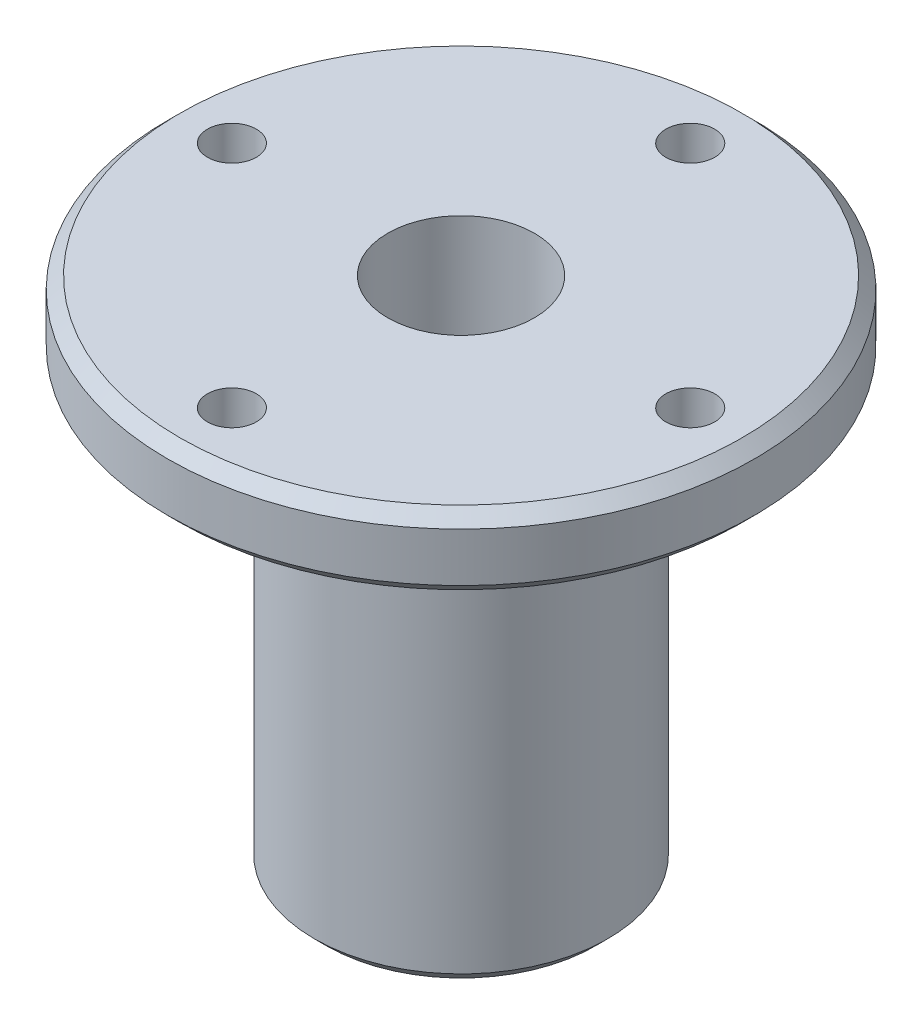
SolidWorks part; units mm, degrees
ref_plane "Front Plane" through (0, 0, 0) normal (0, 0, 1) x (1, 0, 0)
ref_plane "Top Plane" through (0, 0, 0) normal (0, 1, 0) x (1, 0, 0)
ref_plane "Right Plane" through (0, 0, 0) normal (1, 0, 0) x (0, 0, -1)
sketch "Sketch1" plane through (0, 0, 0) normal (0, 1, 0) x (1, 0, 0)
  circle A0 centre (0, 0) radius 6
  circle A1 centre (0, 0) radius 1.35
  dimension "D1" = 12
  dimension "D2" = 2.7
extrude "Eixo" add sketch "Sketch1" along normal blind 18
sketch "Sketch2" plane through (0, 0, 0) normal (0, -1, 0) x (1, 0, 0)
  circle A0 centre (0, 0) radius 1.5
  dimension "D1" = 3
extrude "Rebaixo de Encaixe no Servo" cut sketch "Sketch2" against normal blind 4
sketch "Sketch3" plane through (0, 4, 0) normal (0, -1, 0) x (1, 0, 0)
  circle A0 centre (0, 0) radius 3
  dimension "D1" = 6
extrude "Rebaixo de Encaixe do Parafuso" cut sketch "Sketch3" against normal through all from offset 2 offset against normal yes
sketch "Sketch4" plane through (0, 18, 0) normal (0, 1, 0) x (1, 0, 0)
  line L0 (0, -9.375) -> (0, 9.375) construction
  line L1 (9.375, 0) -> (-9.375, 0) construction
  circle A0 centre (0, 0) radius 12
  circle A1 centre (0, 0) radius 3
  circle A2 centre (0, 0) radius 9.375 construction
  circle A3 centre (0, 9.375) radius 1
  circle A4 centre (9.375, 0) radius 1
  circle A5 centre (0, -9.375) radius 1
  circle A6 centre (-9.375, 0) radius 1
  point P8 (0, 0)
  point P10 (0, 0)
  dimension "D1" = 6
  dimension "D2" = 24
  dimension "D3" = 18.75
  dimension "D4" = 2
extrude "Corpo de Fixação no Antebraço" add sketch "Sketch4" along normal blind 3
fillet "Raio de Alívio - 0.5mm" radius 0.5 1 edges at (0, 18, 6)
chamfer "Chanfros 0.5mm" distance 0.5 angle 45 3 edges at (0, 0, 6) (0, 18, 12) (0, 21, 12)
sketch "Sketch6" plane through (0, 0, 0) normal (0, -1, 0) x (1, 0, 0)
  line L50 (-1.674, -1.8568) -> (-1.6928, -2.3854)
  line L51 (-2.1979, -1.93) -> (-1.674, -1.8568)
  line L52 (-2.0832, -1.3821) -> (-2.2329, -1.8894)
  line L53 (-2.6088, -1.3228) -> (-2.0832, -1.3821)
  line L54 (-2.3615, -0.8206) -> (-2.6326, -1.2748)
  line L55 (-2.8558, -0.6325) -> (-2.3615, -0.8206)
  line L56 (-2.4914, -0.2076) -> (-2.8669, -0.58)
  line L57 (-2.9234, 0.0976) -> (-2.4914, -0.2076)
  line L58 (-2.4647, 0.4185) -> (-2.9211, 0.1512)
  line L59 (-2.8073, 0.8215) -> (-2.4647, 0.4185)
  line L60 (-2.2832, 1.0183) -> (-2.7917, 0.8729)
  line L61 (-2.5148, 1.4939) -> (-2.2832, 1.0183)
  line L62 (-1.9582, 1.5541) -> (-2.4869, 1.5397)
  line L63 (-2.0642, 2.0723) -> (-1.9582, 1.5541)
  line L64 (-1.5102, 1.9923) -> (-2.0259, 2.1098)
  line L65 (-1.484, 2.5206) -> (-1.5102, 1.9923)
  line L66 (-0.9673, 2.3053) -> (-1.4376, 2.5474)
  line L67 (-0.8105, 2.8105) -> (-0.9673, 2.3053)
  line L68 (-0.3636, 2.4734) -> (-0.7589, 2.8248)
  line L69 (-0.0862, 2.9237) -> (-0.3636, 2.4734)
  line L70 (0.2629, 2.4861) -> (-0.0325, 2.9248)
  line L71 (0.6437, 2.8533) -> (0.2629, 2.4861)
  line L72 (0.873, 2.3426) -> (0.6959, 2.841)
  line L73 (1.333, 2.6036) -> (0.873, 2.3426)
  line L74 (1.4281, 2.0519) -> (1.3805, 2.5787)
  line L75 (1.9386, 2.1903) -> (1.4281, 2.0519)
  line L76 (1.8936, 1.6323) -> (1.9785, 2.1544)
  line L77 (2.4224, 1.6394) -> (1.8936, 1.6323)
  line L78 (2.24, 1.1101) -> (2.4521, 1.5947)
  line L79 (2.754, 0.9854) -> (2.24, 1.1101)
  line L80 (2.4457, 0.5182) -> (2.7716, 0.9348)
  line L81 (2.9126, 0.2696) -> (2.4457, 0.5182)
  line L82 (2.4977, -0.1063) -> (2.917, 0.2161)
  line L83 (2.8881, -0.4632) -> (2.4977, -0.1063)
  line L84 (2.3928, -0.7241) -> (2.8791, -0.5161)
  line L85 (2.6822, -1.1669) -> (2.3928, -0.7241)
  line L86 (2.1376, -1.2965) -> (2.6603, -1.2159)
  line L87 (2.3077, -1.7973) -> (2.1376, -1.2965)
  line L88 (1.748, -1.7873) -> (2.2744, -1.8393)
  line L89 (1.7882, -2.3147) -> (1.748, -1.7873)
  line L90 (1.2486, -2.1659) -> (1.7455, -2.3471)
  line L91 (1.1564, -2.6867) -> (1.2486, -2.1659)
  line L92 (0.6707, -2.4083) -> (1.1069, -2.7075)
  line L93 (0.4519, -2.8899) -> (0.6707, -2.4083)
  line L94 (0.0507, -2.4995) -> (0.3989, -2.8977)
  line L95 (-0.281, -2.9115) -> (0.0507, -2.4995)
  line L96 (-0.5725, -2.4336) -> (-0.3343, -2.9058)
  line L97 (-0.9962, -2.7501) -> (-0.5725, -2.4336)
  line L98 (-1.1597, -2.2148) -> (-1.0464, -2.7314)
  line L99 (-1.6488, -2.416) -> (-1.1597, -2.2148)
  line L100 (-1.674, -1.8568) -> (-1.6928, -2.3854)
  line L101 (-2.1979, -1.93) -> (-1.674, -1.8568)
  line L102 (-2.0832, -1.3821) -> (-2.2329, -1.8894)
  line L103 (-2.6088, -1.3228) -> (-2.0832, -1.3821)
  line L104 (-2.3615, -0.8206) -> (-2.6326, -1.2748)
  line L105 (-2.8558, -0.6325) -> (-2.3615, -0.8206)
  line L106 (-2.4914, -0.2076) -> (-2.8669, -0.58)
  line L107 (-2.9234, 0.0976) -> (-2.4914, -0.2076)
  line L108 (-2.4647, 0.4185) -> (-2.9211, 0.1512)
  line L109 (-2.8073, 0.8215) -> (-2.4647, 0.4185)
  line L110 (-2.2832, 1.0183) -> (-2.7917, 0.8729)
  line L111 (-2.5148, 1.4939) -> (-2.2832, 1.0183)
  line L112 (-1.9582, 1.5541) -> (-2.4869, 1.5397)
  line L113 (-2.0642, 2.0723) -> (-1.9582, 1.5541)
  line L114 (-1.5102, 1.9923) -> (-2.0259, 2.1098)
  line L115 (-1.484, 2.5206) -> (-1.5102, 1.9923)
  line L116 (-0.9673, 2.3053) -> (-1.4376, 2.5474)
  line L117 (-0.8105, 2.8105) -> (-0.9673, 2.3053)
  line L118 (-0.3636, 2.4734) -> (-0.7589, 2.8248)
  line L119 (-0.0862, 2.9237) -> (-0.3636, 2.4734)
  line L120 (0.2629, 2.4861) -> (-0.0325, 2.9248)
  line L121 (0.6437, 2.8533) -> (0.2629, 2.4861)
  line L122 (0.873, 2.3426) -> (0.6959, 2.841)
  line L123 (1.333, 2.6036) -> (0.873, 2.3426)
  line L124 (1.4281, 2.0519) -> (1.3805, 2.5787)
  line L125 (1.9386, 2.1903) -> (1.4281, 2.0519)
  line L126 (1.8936, 1.6323) -> (1.9785, 2.1544)
  line L127 (2.4224, 1.6394) -> (1.8936, 1.6323)
  line L128 (2.24, 1.1101) -> (2.4521, 1.5947)
  line L129 (2.754, 0.9854) -> (2.24, 1.1101)
  line L130 (2.4457, 0.5182) -> (2.7716, 0.9348)
  line L131 (2.9126, 0.2696) -> (2.4457, 0.5182)
  line L132 (2.4977, -0.1063) -> (2.917, 0.2161)
  line L133 (2.8881, -0.4632) -> (2.4977, -0.1063)
  line L134 (2.3928, -0.7241) -> (2.8791, -0.5161)
  line L135 (2.6822, -1.1669) -> (2.3928, -0.7241)
  line L136 (2.1376, -1.2965) -> (2.6603, -1.2159)
  line L137 (2.3077, -1.7973) -> (2.1376, -1.2965)
  line L138 (1.748, -1.7873) -> (2.2744, -1.8393)
  line L139 (1.7882, -2.3147) -> (1.748, -1.7873)
  line L140 (1.2486, -2.1659) -> (1.7455, -2.3471)
  line L141 (1.1564, -2.6867) -> (1.2486, -2.1659)
  line L142 (0.6707, -2.4083) -> (1.1069, -2.7075)
  line L143 (0.4519, -2.8899) -> (0.6707, -2.4083)
  line L144 (0.0507, -2.4995) -> (0.3989, -2.8977)
  line L145 (-0.281, -2.9115) -> (0.0507, -2.4995)
  line L146 (-0.5725, -2.4336) -> (-0.3343, -2.9058)
  line L147 (-0.9962, -2.7501) -> (-0.5725, -2.4336)
  line L148 (-1.1597, -2.2148) -> (-1.0464, -2.7314)
  line L149 (-1.6488, -2.416) -> (-1.1597, -2.2148)
  arc A25 (-1.6928, -2.3854) -> (-1.6488, -2.416) centre (0, 0) ccw
  arc A26 (-2.2329, -1.8894) -> (-2.1979, -1.93) centre (0, 0) ccw
  arc A27 (-2.6326, -1.2748) -> (-2.6088, -1.3228) centre (0, 0) ccw
  arc A28 (-2.8669, -0.58) -> (-2.8558, -0.6325) centre (0, 0) ccw
  arc A29 (-2.9211, 0.1512) -> (-2.9234, 0.0976) centre (0, 0) ccw
  arc A30 (-2.7917, 0.8729) -> (-2.8073, 0.8215) centre (0, 0) ccw
  arc A31 (-2.4869, 1.5397) -> (-2.5148, 1.4939) centre (0, 0) ccw
  arc A32 (-2.0259, 2.1098) -> (-2.0642, 2.0723) centre (0, 0) ccw
  arc A33 (-1.4376, 2.5474) -> (-1.484, 2.5206) centre (0, 0) ccw
  arc A34 (-0.7589, 2.8248) -> (-0.8105, 2.8105) centre (0, 0) ccw
  arc A35 (-0.0325, 2.9248) -> (-0.0862, 2.9237) centre (0, 0) ccw
  arc A36 (0.6959, 2.841) -> (0.6437, 2.8533) centre (0, 0) ccw
  arc A37 (1.3805, 2.5787) -> (1.333, 2.6036) centre (0, 0) ccw
  arc A38 (1.9785, 2.1544) -> (1.9386, 2.1903) centre (0, 0) ccw
  arc A39 (2.4521, 1.5947) -> (2.4224, 1.6394) centre (0, 0) ccw
  arc A40 (2.7716, 0.9348) -> (2.754, 0.9854) centre (0, 0) ccw
  arc A41 (2.917, 0.2161) -> (2.9126, 0.2696) centre (0, 0) ccw
  arc A42 (2.8791, -0.5161) -> (2.8881, -0.4632) centre (0, 0) ccw
  arc A43 (2.6603, -1.2159) -> (2.6822, -1.1669) centre (0, 0) ccw
  arc A44 (2.2744, -1.8393) -> (2.3077, -1.7973) centre (0, 0) ccw
  arc A45 (1.7455, -2.3471) -> (1.7882, -2.3147) centre (0, 0) ccw
  arc A46 (1.1069, -2.7075) -> (1.1564, -2.6867) centre (0, 0) ccw
  arc A47 (0.3989, -2.8977) -> (0.4519, -2.8899) centre (0, 0) ccw
  arc A48 (-0.3343, -2.9058) -> (-0.281, -2.9115) centre (0, 0) ccw
  arc A49 (-1.0464, -2.7314) -> (-0.9962, -2.7501) centre (0, 0) ccw
  arc A50 (-1.6928, -2.3854) -> (-1.6488, -2.416) centre (0, 0) ccw
  arc A51 (-2.2329, -1.8894) -> (-2.1979, -1.93) centre (0, 0) ccw
  arc A52 (-2.6326, -1.2748) -> (-2.6088, -1.3228) centre (0, 0) ccw
  arc A53 (-2.8669, -0.58) -> (-2.8558, -0.6325) centre (0, 0) ccw
  arc A54 (-2.9211, 0.1512) -> (-2.9234, 0.0976) centre (0, 0) ccw
  arc A55 (-2.7917, 0.8729) -> (-2.8073, 0.8215) centre (0, 0) ccw
  arc A56 (-2.4869, 1.5397) -> (-2.5148, 1.4939) centre (0, 0) ccw
  arc A57 (-2.0259, 2.1098) -> (-2.0642, 2.0723) centre (0, 0) ccw
  arc A58 (-1.4376, 2.5474) -> (-1.484, 2.5206) centre (0, 0) ccw
  arc A59 (-0.7589, 2.8248) -> (-0.8105, 2.8105) centre (0, 0) ccw
  arc A60 (-0.0325, 2.9248) -> (-0.0862, 2.9237) centre (0, 0) ccw
  arc A61 (0.6959, 2.841) -> (0.6437, 2.8533) centre (0, 0) ccw
  arc A62 (1.3805, 2.5787) -> (1.333, 2.6036) centre (0, 0) ccw
  arc A63 (1.9785, 2.1544) -> (1.9386, 2.1903) centre (0, 0) ccw
  arc A64 (2.4521, 1.5947) -> (2.4224, 1.6394) centre (0, 0) ccw
  arc A65 (2.7716, 0.9348) -> (2.754, 0.9854) centre (0, 0) ccw
  arc A66 (2.917, 0.2161) -> (2.9126, 0.2696) centre (0, 0) ccw
  arc A67 (2.8791, -0.5161) -> (2.8881, -0.4632) centre (0, 0) ccw
  arc A68 (2.6603, -1.2159) -> (2.6822, -1.1669) centre (0, 0) ccw
  arc A69 (2.2744, -1.8393) -> (2.3077, -1.7973) centre (0, 0) ccw
  arc A70 (1.7455, -2.3471) -> (1.7882, -2.3147) centre (0, 0) ccw
  arc A71 (1.1069, -2.7075) -> (1.1564, -2.6867) centre (0, 0) ccw
  arc A72 (0.3989, -2.8977) -> (0.4519, -2.8899) centre (0, 0) ccw
  arc A73 (-0.3343, -2.9058) -> (-0.281, -2.9115) centre (0, 0) ccw
  arc A74 (-1.0464, -2.7314) -> (-0.9962, -2.7501) centre (0, 0) ccw
  dimension "D1" = 0
extrude "Encaixe da Engrenagem do Servo" cut sketch "Sketch6" against normal blind 4
